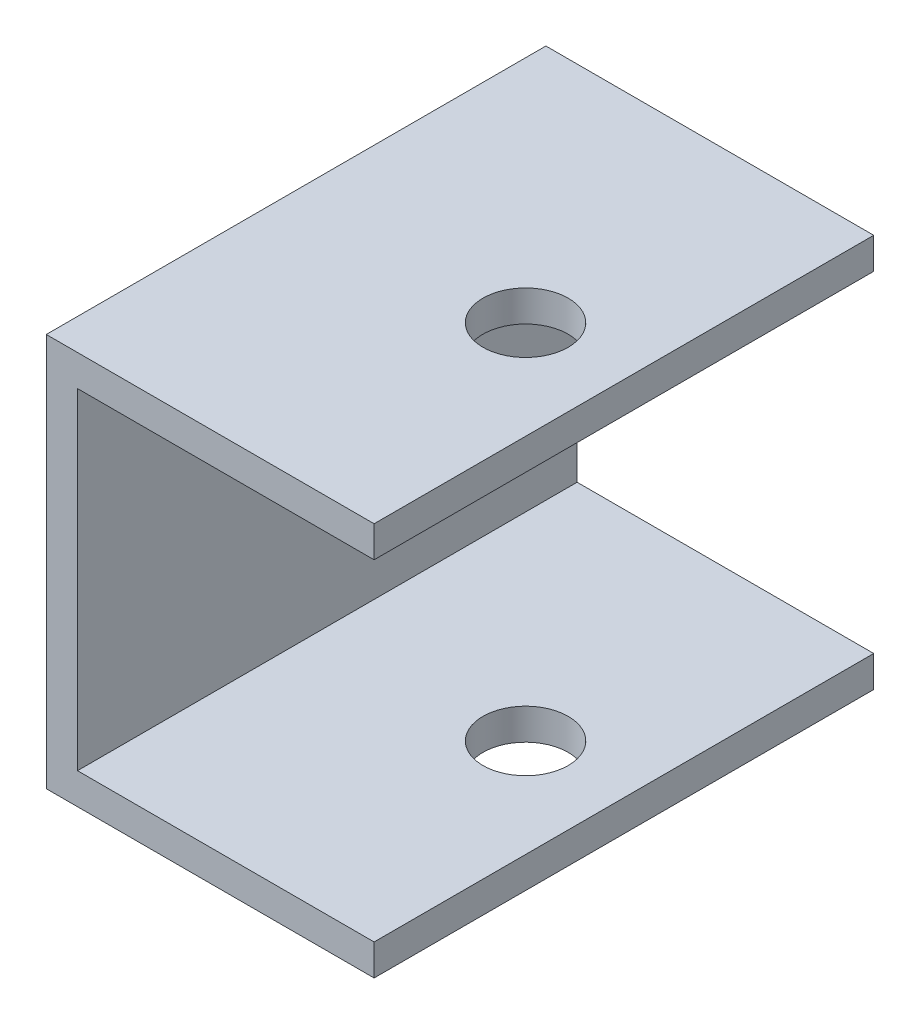
SolidWorks part; units mm, degrees
material "AISI 1020 Acero laminado en frío"
ref_plane "Alzado" through (0, 0, 0) normal (0, 0, 1) x (1, 0, 0)
ref_plane "Planta" through (0, 0, 0) normal (0, 1, 0) x (1, 0, 0)
ref_plane "Vista lateral" through (0, 0, 0) normal (1, 0, 0) x (0, 0, -1)
sketch "Croquis6" plane through (0, 0, 0) normal (0, 0, 1) x (1, 0, 0)
  line L0 (45.2375, 25.2375) -> (0, 25.2375)
  line L1 (0, 25.2375) -> (0, -25.2375)
  line L2 (0, -25.2375) -> (45.2375, -25.2375)
  line L3 (45.2375, -25.2375) -> (45.2375, -30)
  line L4 (45.2375, -30) -> (-4.7625, -30)
  line L5 (-4.7625, -30) -> (-4.7625, 30)
  line L6 (-4.7625, 30) -> (45.2375, 30)
  line L7 (45.2375, 30) -> (45.2375, 25.2375)
  point P3 (0, 0)
  dimension "D1" = 4.7625
  dimension "D2" = 4.7625
  dimension "D3" = 4.7625
  dimension "D4" = 60
  dimension "D5" = 50
extrude "Saliente-Extruir3" add sketch "Croquis6" along normal mid plane 76.2
sketch "Croquis7" plane through (-4.7625, 0, 0) normal (-1, 0, 0) x (0, 0, 1)
  circle A0 centre (0, 0) radius 5.5562
  dimension "D1" = 11.1125
extrude "Cortar-Extruir1" cut sketch "Croquis7" against normal blind 5 contours A0
sketch "Croquis8" plane through (0, -30, 0) normal (0, -1, 0) x (1, 0, 0)
  line L0 (0, 0) -> (31.2543, 0) construction
  line L3 (45.2375, 38.1) -> (45.2375, -38.1) construction
  circle A0 centre (30.2375, 0) radius 6.5
  point P4 (0, 0)
  point P7 (0, 0)
  dimension "D1" = 13
  dimension "D2" = 15
extrude "Cortar-Extruir2" cut sketch "Croquis8" against normal blind 70 contours A0
